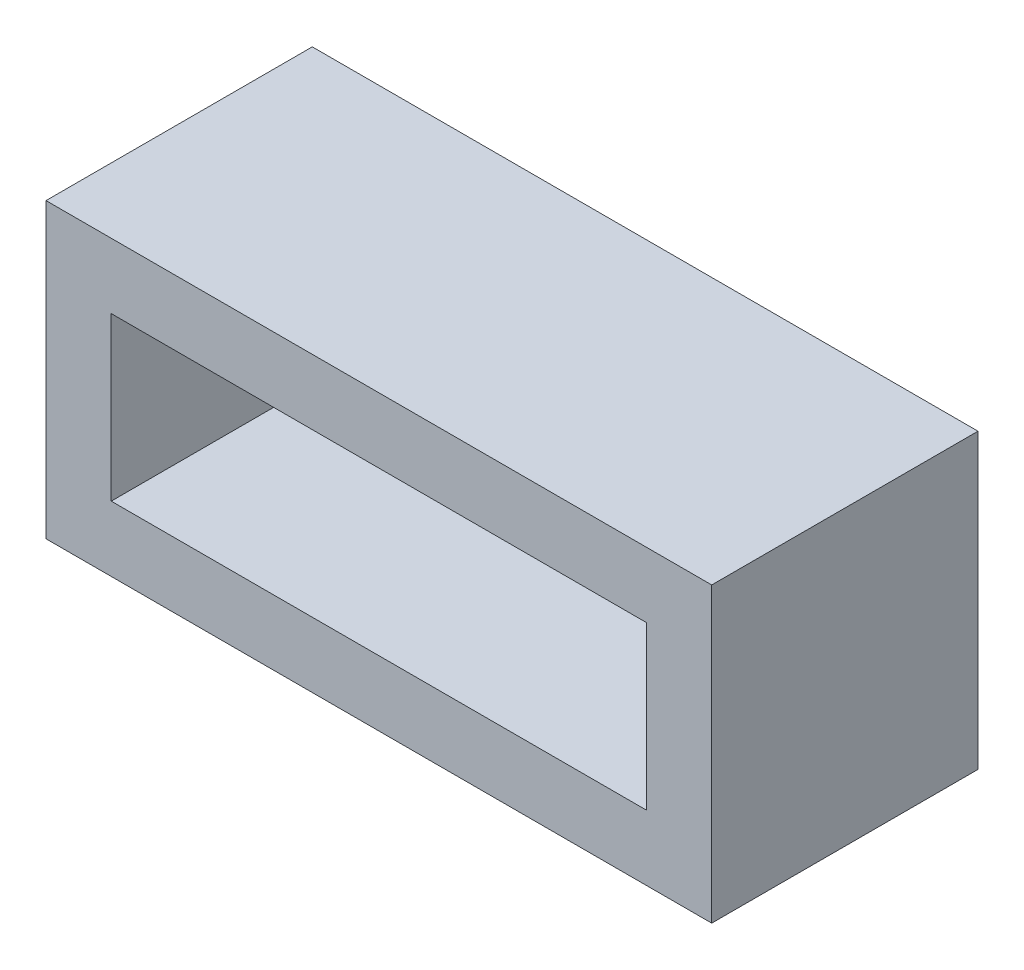
SolidWorks part; units mm, degrees
ref_plane "Front Plane" through (0, 0, 0) normal (0, 0, 1) x (1, 0, 0)
ref_plane "Top Plane" through (0, 0, 0) normal (0, 1, 0) x (1, 0, 0)
ref_plane "Right Plane" through (0, 0, 0) normal (1, 0, 0) x (0, 0, -1)
sketch "Sketch1" plane through (0, 0, 0) normal (0, 0, 1) x (1, 0, 0)
  line L1 (-10.05, -3.05) -> (10.05, -3.05)
  line L2 (-10.05, -3.05) -> (-10.05, 3.05)
  line L3 (-10.05, 3.05) -> (10.05, 3.05)
  line L4 (10.05, -3.05) -> (10.05, 3.05)
  line L5 (-10.05, -3.05) -> (10.05, 3.05) construction
  line L6 (-10.05, 3.05) -> (10.05, -3.05) construction
  line L7 (-12.5, -5.5) -> (12.5, -5.5)
  line L8 (-12.5, -5.5) -> (-12.5, 5.5)
  line L9 (-12.5, 5.5) -> (12.5, 5.5)
  line L10 (12.5, -5.5) -> (12.5, 5.5)
  line L11 (-12.5, -5.5) -> (12.5, 5.5) construction
  line L12 (-12.5, 5.5) -> (12.5, -5.5) construction
  point P0 (0, 0)
  point P6 (0, 0)
  dimension "D1" = 20.1
  dimension "D2" = 6.1
  dimension "D3" = 25
  dimension "D4" = 11
extrude "Boss-Extrude1" add sketch "Sketch1" along normal blind 10
